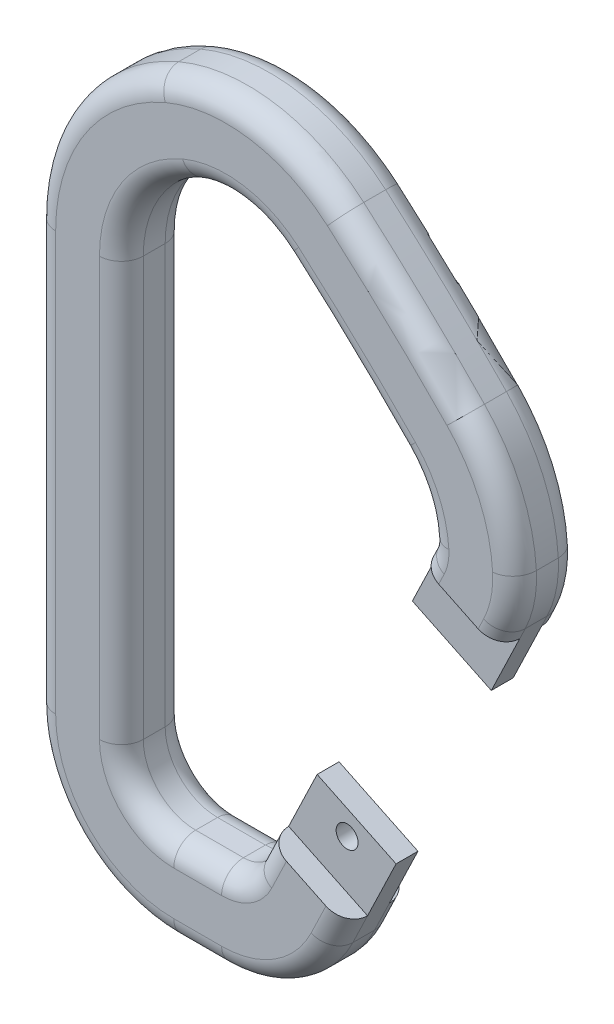
SolidWorks part; units mm, degrees
ref_plane "Front Plane" through (0, 0, 0) normal (0, 0, 1) x (1, 0, 0)
ref_plane "Top Plane" through (0, 0, 0) normal (0, 1, 0) x (1, 0, 0)
ref_plane "Right Plane" through (0, 0, 0) normal (1, 0, 0) x (0, 0, -1)
sketch "Sketch1" plane through (0, 0, 0) normal (0, 0, 1) x (1, 0, 0)
  line L0 (502.9761, 910.2275) -> (553.7761, 910.2275) construction
sketch "Sketch2" plane through (0, 0, 0) normal (0, 0, 1) x (1, 0, 0)
  line L0 (507.9828, 929.8561) -> (507.9828, 881.3107) construction
  line L1 (519.1419, 870.1611) -> (524.6907, 870.1658) construction
  line L2 (532.7912, 875.2608) -> (534.5011, 878.8117) construction
  line L3 (552.7915, 916.7968) -> (552.1579, 915.4808) construction
  line L4 (557.3686, 914.5929) -> (556.7349, 913.2768)
  line L5 (502.9028, 929.8561) -> (502.9028, 881.3107)
  line L6 (519.1462, 865.0811) -> (524.695, 865.0858)
  line L7 (537.3683, 873.0568) -> (539.0781, 876.6078)
  line L8 (547.5808, 917.6847) -> (556.7349, 913.2768)
  line L9 (529.9241, 881.0156) -> (539.0781, 876.6078)
  line L12 (548.2145, 919.0007) -> (547.5808, 917.6847)
  line L13 (513.0628, 929.8561) -> (513.0628, 881.3107)
  line L14 (519.1376, 875.2411) -> (524.6863, 875.2458)
  line L16 (528.2142, 877.4647) -> (529.9241, 881.0156)
  arc A0 (507.9828, 881.3107) -> (519.1419, 870.1611) centre (519.1324, 881.3107) ccw construction
  arc A1 (524.6907, 870.1658) -> (532.7912, 875.2608) centre (524.683, 879.165) ccw construction
  arc A2 (507.9828, 929.8561) -> (519.1703, 946.7723) centre (526.3658, 929.8561) cw construction
  arc A3 (519.1703, 946.7723) -> (535.2976, 944.2107) centre (525.1896, 932.6212) cw construction
  arc A4 (535.2976, 944.2107) -> (549.0006, 931.2304) centre (384.3184, 771.1021) cw construction
  arc A5 (549.0006, 931.2304) -> (553.5852, 920.7823) centre (537.3242, 919.8769) cw construction
  arc A6 (558.6574, 921.0647) -> (557.3686, 914.5929) centre (545.4547, 920.3296) cw
  arc A7 (552.6427, 934.7718) -> (558.6574, 921.0647) centre (537.3242, 919.8769) cw
  arc A8 (538.6367, 948.0391) -> (552.6427, 934.7718) centre (384.3184, 771.1021) cw
  arc A9 (517.1818, 951.447) -> (538.6367, 948.0391) centre (525.1896, 932.6212) cw
  arc A10 (502.9028, 929.8561) -> (517.1818, 951.447) centre (526.3658, 929.8561) cw
  arc A11 (502.9028, 881.3107) -> (519.1462, 865.0811) centre (519.1324, 881.3107) ccw
  arc A12 (524.695, 865.0858) -> (537.3683, 873.0568) centre (524.683, 879.165) ccw
  arc A19 (553.5852, 920.7823) -> (552.7915, 916.7968) centre (545.4547, 920.3296) cw construction
  arc A20 (548.5131, 920.4999) -> (548.2145, 919.0007) centre (545.4547, 920.3296) cw
  arc A24 (545.3585, 927.689) -> (548.5131, 920.4999) centre (537.3242, 919.8769) cw
  arc A25 (531.9586, 940.3822) -> (545.3585, 927.689) centre (384.3184, 771.1021) cw
  arc A26 (521.1587, 942.0976) -> (531.9586, 940.3822) centre (525.1896, 932.6212) cw
  arc A27 (513.0628, 929.8561) -> (521.1587, 942.0976) centre (526.3658, 929.8561) cw
  arc A28 (513.0628, 881.3107) -> (519.1376, 875.2411) centre (519.1324, 881.3107) ccw
  arc A29 (524.6863, 875.2458) -> (528.2142, 877.4647) centre (524.683, 879.165) ccw
  dimension "D1" = 5.08
  dimension "D3" = 5.08
extrude "Boss-Extrude1" add sketch "Sketch2" along normal blind 7.62
move or copy body "Body-Move/Copy1" bodies to move or copy 101 copy no translate (-502.9028, -881.3107, 0)
fillet "Fillet1" radius 2.54 44 edges at (54.1489, 32.6242, 0) (55.5204, 36.4364, 0) (53.9868, 47.1515, 0) (42.8732, 60.2387, 0) (25.4961, 71.5154, 0) (3.8927, 61.4881, 0) (35.3204, -6.4783, 0) (29.2762, -14.0635, 0) (19.0178, -16.2273, 0) (4.7584, -11.4809, 0) (35.3204, -6.4783, 7.62) (29.2762, -14.0635, 7.62) (19.0178, -16.2273, 7.62) (4.7584, -11.4809, 7.62) (0, 24.2727, 7.62) (54.1489, 32.6242, 7.62) (55.5204, 36.4364, 7.62) (53.9868, 47.1515, 7.62) (42.8732, 60.2387, 7.62) (25.4961, 71.5154, 7.62) (0, 24.2727, 0) (3.8927, 61.4881, 7.62) (44.9949, 37.032, 0) (45.556, 38.4207, 0) (44.6831, 43.0691, 0) (35.8861, 52.8626, 0) (23.9023, 61.4812, 0) (12.3671, 55.8837, 0) (26.1663, -2.0705, 0) (23.8669, -5.4632, 0) (19.0091, -6.0673, 0) (11.9396, -4.2937, 0) (26.1663, -2.0705, 7.62) (23.8669, -5.4632, 7.62) (19.0091, -6.0673, 7.62) (11.9396, -4.2937, 7.62) (10.16, 24.2727, 7.62) (44.9949, 37.032, 7.62) (45.556, 38.4207, 7.62) (44.6831, 43.0691, 7.62) (35.8861, 52.8626, 7.62) (23.9023, 61.4812, 7.62) (10.16, 24.2727, 0) (12.3671, 55.8837, 7.62)
sketch "Sketch4" plane through (22.6274, 46.9918, 0) normal (-0.4338, -0.901, 0) x (0.901, -0.4338, 0)
  line L1 (24.4738, 5.08) -> (34.6338, 5.08)
  line L2 (24.4738, 5.08) -> (24.4738, 2.54)
  line L3 (24.4738, 2.54) -> (34.6338, 2.54)
  line L4 (34.6338, 5.08) -> (34.6338, 2.54)
extrude "Boss-Extrude2" add sketch "Sketch4" along normal up to surface (40.6987 mm away) up to face at (31.5983, -2.4989, 3.81)
sketch "Sketch5" plane through (0, 0, 5.08) normal (0, 0, 1) x (1, 0, 0)
  line L0 (41.3721, 29.5085) -> (50.5262, 25.1006)
  line L1 (27.0212, -0.295) -> (44.678, 36.374) construction
  line L2 (36.1753, -4.7029) -> (53.8321, 31.9662) construction
  line L3 (50.5262, 25.1006) -> (39.4812, 2.1627)
  line L4 (39.4812, 2.1627) -> (30.3271, 6.5705)
  line L5 (30.3271, 6.5705) -> (41.3721, 29.5085)
  line L6 (46.9665, 35.2721) -> (51.5436, 33.0681) construction
  line L8 (29.3098, -1.397) -> (33.8868, -3.6009) construction
  dimension "D1" = 7.62
  dimension "D2" = 7.62
extrude "Cut-Extrude1" cut sketch "Sketch5" against normal through all both and the other way through all contours L4 L5 L0 L3
sketch "Sketch7" plane through (0, 0, 0) normal (0, 0, 1) x (1, 0, 0)
  line L1 (30.3271, 6.5705) -> (39.4812, 2.1627) construction
  line L2 (31.5983, -2.4989) -> (34.9041, 4.3666) construction
  line L3 (29.3098, -1.397) -> (33.8868, -3.6009) construction
  circle A1 centre (33.8022, 2.0781) radius 1.27
  point P6 (0, 0)
  dimension "D1" = 2.54
  dimension "D2" = 2.54
extrude "Cut-Extrude2" cut sketch "Sketch7" along normal through all
